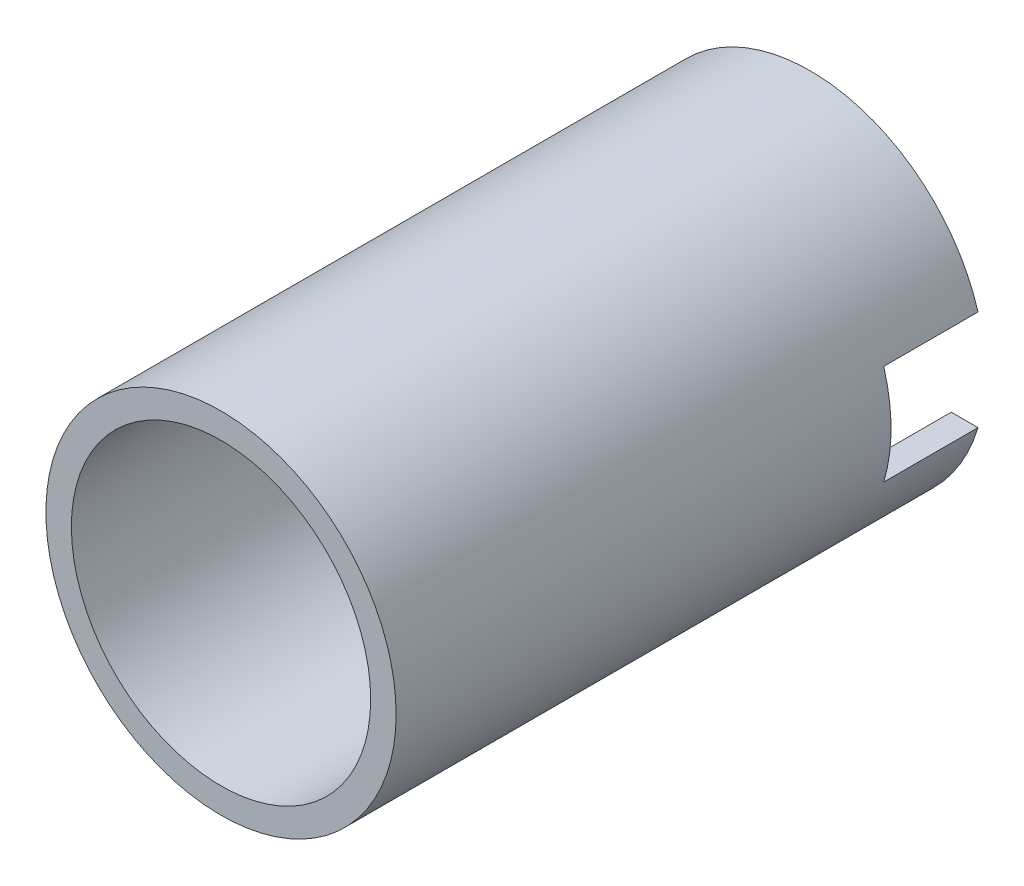
SolidWorks part; units mm, degrees
ref_plane "Alzado" through (0, 0, 0) normal (0, 0, 1) x (1, 0, 0)
ref_plane "Planta" through (0, 0, 0) normal (0, 1, 0) x (1, 0, 0)
ref_plane "Vista lateral" through (0, 0, 0) normal (1, 0, 0) x (0, 0, -1)
sketch "Croquis1" plane through (0, 0, 0) normal (0, 0, 1) x (1, 0, 0)
  circle A0 centre (0, 0) radius 25.4
  circle A1 centre (0, 0) radius 29.72
  dimension "D1" = 59.44
  dimension "D2" = 50.8
extrude "Saliente-Extruir1" add sketch "Croquis1" along normal blind 100
sketch "Croquis3" plane through (0, 0, 0) normal (1, 0, 0) x (0, 0, -1)
  line L0 (0, 21) -> (-21, 21)
  line L1 (0, -29.72) -> (0, 29.72) construction
  line L2 (-21, -21) -> (0, -21)
  line L3 (0, -21) -> (0, 21)
  arc A0 (-21, 21) -> (-21, -21) centre (-21, 0) ccw
  point P11 (-42, 0)
  dimension "D1" = 21
  dimension "D2" = 42
extrude "Cortar-Extruir2" cut sketch "Croquis3" against normal through all
sketch "Croquis4" plane through (0, 0, 0) normal (1, 0, 0) x (0, 0, -1)
  line L0 (0, -29.72) -> (0, 29.72) construction
  line L1 (0, -8.5) -> (-16, -8.5)
  line L2 (0, -8.5) -> (0, 8.5)
  line L3 (0, 8.5) -> (-16, 8.5)
  line L4 (-16, -8.5) -> (-16, 8.5)
  line L5 (0, -8.5) -> (-16, 8.5) construction
  line L6 (0, 8.5) -> (-16, -8.5) construction
  point P0 (-8, 0)
  dimension "D1" = 16
  dimension "D2" = 17
extrude "Cortar-Extruir3" cut sketch "Croquis4" along normal through all
